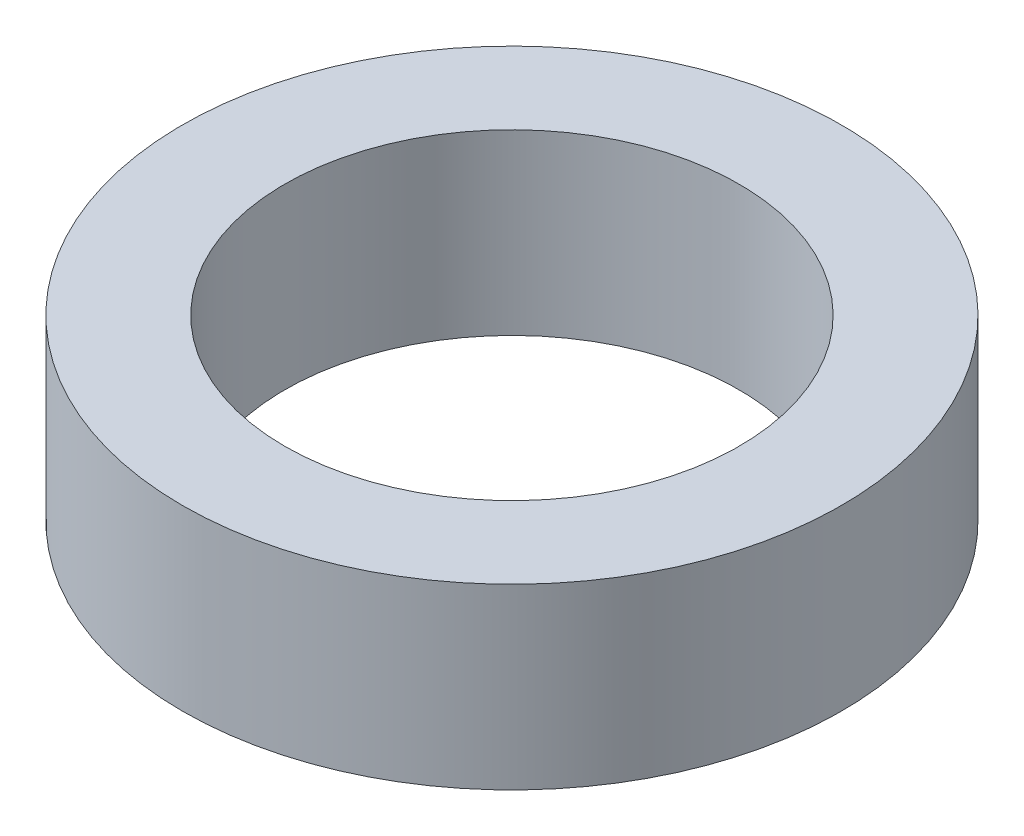
SolidWorks part; units mm, degrees
ref_plane "Alzado" through (0, 0, 0) normal (0, 0, 1) x (1, 0, 0)
ref_plane "Planta" through (0, 0, 0) normal (0, 1, 0) x (1, 0, 0)
ref_plane "Vista lateral" through (0, 0, 0) normal (1, 0, 0) x (0, 0, -1)
sketch "Croquis1" plane through (0, 0, 0) normal (0, 1, 0) x (1, 0, 0)
  circle A0 centre (0, 0) radius 5.1
  circle A1 centre (0, 0) radius 7.4
  dimension "D1" = 14.8
  dimension "D2" = 10.2
extrude "Saliente-Extruir1" add sketch "Croquis1" along normal blind 4
